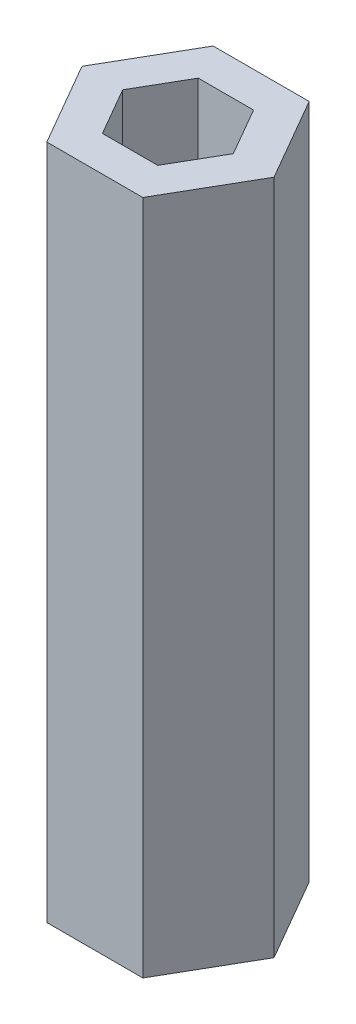
SolidWorks part; units mm, degrees
ref_plane "Front Plane" through (0, 0, 0) normal (0, 0, 1) x (1, 0, 0)
ref_plane "Top Plane" through (0, 0, 0) normal (0, 1, 0) x (1, 0, 0)
ref_plane "Right Plane" through (0, 0, 0) normal (1, 0, 0) x (0, 0, -1)
sketch "Sketch1" plane through (0, 0, 0) normal (0, 1, 0) x (1, 0, 0)
  line L1 (3.6084, 6.25) -> (-3.6084, 6.25)
  line L2 (-3.6084, 6.25) -> (-7.2169, 0)
  line L3 (-7.2169, 0) -> (-3.6084, -6.25)
  line L4 (-3.6084, -6.25) -> (3.6084, -6.25)
  line L5 (3.6084, -6.25) -> (7.2169, 0)
  line L6 (7.2169, 0) -> (3.6084, 6.25)
  line L7 (2.0785, 3.6) -> (-2.0785, 3.6)
  line L8 (-2.0785, 3.6) -> (-4.1569, 0)
  line L9 (-4.1569, 0) -> (-2.0785, -3.6)
  line L10 (-2.0785, -3.6) -> (2.0785, -3.6)
  line L11 (2.0785, -3.6) -> (4.1569, 0)
  line L12 (4.1569, 0) -> (2.0785, 3.6)
  circle A0 centre (0, 0) radius 6.25 construction
  circle A1 centre (0, 0) radius 3.6 construction
  dimension "D1" = 7.2
  dimension "D2" = 12.5
extrude "Boss-Extrude1" add sketch "Sketch1" along normal blind 50.8
